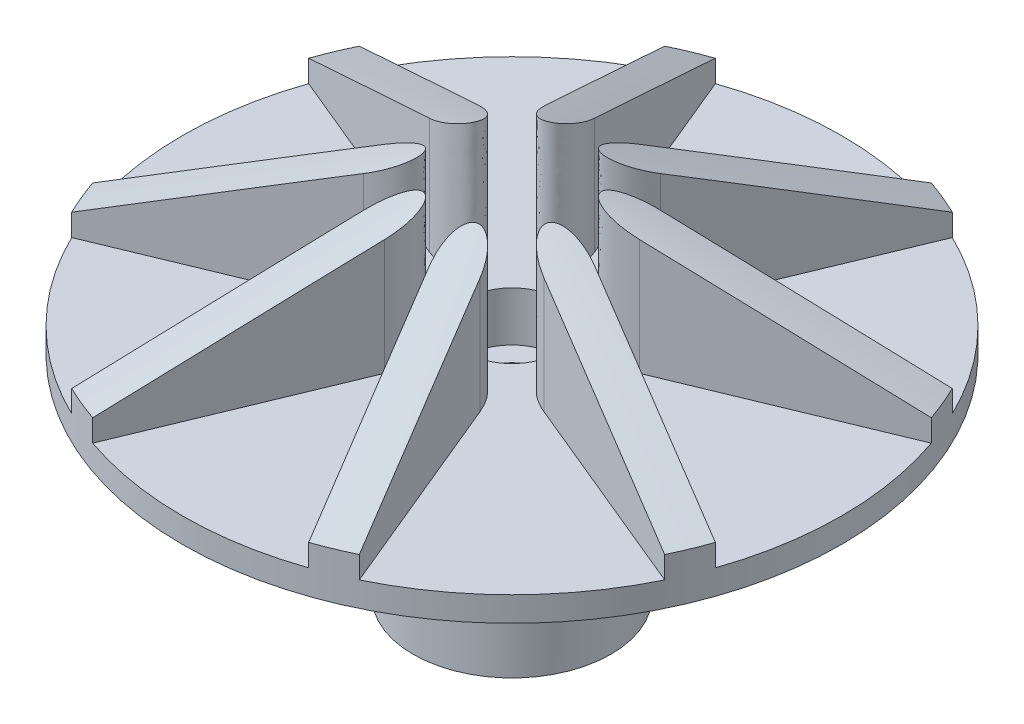
SolidWorks part; units mm, degrees
ref_plane "Front Plane" through (0, 0, 0) normal (0, 0, 1) x (1, 0, 0)
ref_plane "Top Plane" through (0, 0, 0) normal (0, 1, 0) x (1, 0, 0)
ref_plane "Right Plane" through (0, 0, 0) normal (1, 0, 0) x (0, 0, -1)
sketch "Sketch1" plane through (0, 0, 0) normal (0, 1, 0) x (1, 0, 0)
  circle A0 centre (0, 0) radius 26.6319
  dimension "D1" = 53.2638
extrude "impeller plate" add sketch "Sketch1" along normal blind 2
sketch "Sketch6" plane through (0, 0, 0) normal (0, -1, 0) x (-1, 0, 0)
  circle A0 centre (0, 0) radius 8
  dimension "D1" = 16
extrude "boss" add sketch "Sketch6" along normal blind 17
sketch "Sketch7" plane through (0, -17, 0) normal (0, -1, 0) x (-1, 0, 0)
  circle A0 centre (0, 0) radius 2
  dimension "D1" = 4
extrude "bolt bore" cut sketch "Sketch7" against normal through all
sketch "Sketch8" plane through (0, -17, 0) normal (0, -1, 0) x (-1, 0, 0)
  circle A0 centre (0, 0) radius 4
  dimension "D1" = 8
extrude "shaft bore" cut sketch "Sketch8" against normal blind 12
sketch "Sketch9" plane through (0, 2, 0) normal (0, 1, 0) x (1, 0, 0)
  circle A0 centre (0, 0) radius 3.75
  dimension "D1" = 7.5
extrude "bolt head bore" cut sketch "Sketch9" against normal blind 4
sketch "Sketch11" plane through (0, -17, 0) normal (0, -1, 0) x (1, 0, 0)
  line L1 (-6, 1) -> (6, 1)
  line L2 (-6, 1) -> (-6, -1)
  line L3 (-6, -1) -> (6, -1)
  line L4 (6, 1) -> (6, -1)
  line L5 (-6, 1) -> (6, -1) construction
  line L6 (-6, -1) -> (6, 1) construction
  point P0 (0, 0)
  dimension "D1" = 12
  dimension "D2" = 2
extrude "dowel slot" cut sketch "Sketch11" against normal blind 3
sketch "Sketch12" plane through (0, 2, 0) normal (0, 1, 0) x (1, 0, 0)
  line L0 (0, 0) -> (26.6319, 0) construction
  line L1 (5.2287, 1.3897) -> (26.5956, 1.3897)
  line L2 (5.2287, -1.3897) -> (26.5956, -1.3897)
  circle A0 centre (0, 0) radius 26.6319 construction
  arc A3 (26.5956, -1.3897) -> (26.5956, 1.3897) centre (0, 0) ccw
  arc A4 (5.2287, -1.3897) -> (5.2287, 1.3897) centre (0, 0) ccw
  dimension "D3" = 10.8204
  dimension "D1" = 1.3897
  dimension "D2" = 1.3897
extrude "opening alingment cut" cut sketch "Sketch12" against normal blind 1
pattern_circular "opening alingment pattern" count 8 over 360 about axis through (0, 0, 0) along (0, 1, 0) of "opening alingment cut"
sketch "Sketch14" plane through (0, 2, 0) normal (0, 1, 0) x (1, 0, 0)
  line L0 (0, 0) -> (26.6319, 0) construction
  line L1 (26.5956, 1.3897) -> (5.2287, 1.3897) construction
  line L2 (7.2942, 4.7175) -> (8.4935, 1.822) construction
  line L3 (25.1617, 8.7262) -> (8.4935, 1.822) construction
  line L4 (7.8938, 3.2697) -> (4.9984, 2.0704) construction
  line L5 (0, 0) -> (24.6047, 10.1916) construction
  line L7 (7.2942, 4.7175) -> (23.9624, 11.6217)
  line L9 (8.4935, 1.822) -> (25.1617, 8.7262)
  arc A2 (26.5956, -1.3897) -> (26.5956, 1.3897) centre (0, 0) ccw construction
  arc A5 (26.5956, 1.3897) -> (19.7886, 17.8232) centre (0, 0) ccw construction
  circle A6 centre (0, 0) radius 5.4102 construction
  circle A7 centre (0, 0) radius 5.4102 construction
  arc A8 (25.1617, 8.7262) -> (23.9624, 11.6217) centre (0, 0) ccw
  ellipse E0 centre (7.8938, 3.2697) end of major axis (10.7893, 4.4691) minor radius 1.567 (7.2942, 4.7175) -> (8.4935, 1.822) ccw
  dimension "D1" = 22.5
extrude "one blade" add sketch "Sketch14" along normal blind 10.7467
sketch "Sketch15" plane through (0, 2, 0) normal (0, 1, 0) x (1, 0, 0)
  circle A0 centre (0, 0) radius 26.6319
  arc A1 (-19.7886, 17.8232) -> (-26.5956, 1.3897) centre (0, 0) ccw construction
  circle A2 centre (0, 0) radius 3.75
  circle A3 centre (0, 0) radius 3.75 construction
extrude "opening alignment fill" add sketch "Sketch15" against normal blind 2
pattern_circular "CirPattern2" count 8 over 360 of "one blade"
sketch "Sketch16" plane through (0, 0, 0) normal (1, 0, 0) x (0, 0, -1)
  line L0 (0, 0) -> (0, 12.7467) construction
  line L2 (26.6319, 0) -> (26.6319, 3.778) construction
  line L3 (0, 12.7467) -> (5.4102, 12.7467) construction
  line L4 (5.4102, 12.7467) -> (26.6319, 3.778)
  line L5 (26.6319, 3.778) -> (26.6319, 12.7467)
  line L6 (26.6319, 12.7467) -> (5.4102, 12.7467)
  line L7 (-26.6319, 0) -> (26.6319, 0) construction
  dimension "D1" = 3.778
  dimension "D2" = 5.4102
  dimension "D3" = 26.6319
  dimension "D4" = 12.7467
revolve "angle cut" cut sketch "Sketch16" angle 360 about L0
equation "\"big seal ID\"= 16mm"
equation "\"z\" = 8 \t\t\t'number of blades"
equation "\"de_length\" = 10mm\t\t'entrance eye consistent length"
equation "\"av\" = \"ae\"*\"av_ratio\"\t\t'area between just two blades"
equation "\"d2\" = 2.097in \t\t\t'outer diameter of the impeller"
equation "\"d_exit\" = 0.18in \t\t'volute throat aka D4"
equation "\"theta\" = 25\t\t\t'angle of blades from inner to outer "
equation "\"b2\" = .07in\t\t\t\t\t\t\t'tip height from disc surface at d2"
equation "\"b1\" = \"b2\" + (\"d2\"/2 - \"de\"/2)*sin(\"theta\") \t\t\t'tip height from disc surface at inlet eye"
equation "\"impeller base thickness\"= 2mm"
equation "\"impeller dowel diameter\" = 2mm"
equation "\"impeller bolt head diameter\" = 7.5mm"
equation "\"impeller bolt head depth\" = 4mm"
equation "\"impeller bolt stop depth\" = 3mm"
equation "\"impeller bolt bore\" = 4mm"
equation "\"impeller shaft bore depth\" = 12mm"
equation "\"impeller shaft bore\" = 8mm"
equation "\"impeller boss depth\" = \"impeller shaft bore depth\"+\"impeller bolt stop depth\"+\"impeller bolt head depth\"-\"impeller base thickness\""
equation "\"impeller boss diameter\" = 16mm"
equation "\"impeller dowel length\" = 2mm*2 + \"impeller shaft bore\""
equation "\"D1@Sketch1\"=\"d2\""
equation "\"D1@impeller plate\" = \"impeller base thickness\""
equation "\"D1@Sketch6\"=\"impeller boss diameter\""
equation "\"D1@boss\" = \"impeller boss depth\""
equation "\"D1@Sketch7\"=\"impeller bolt bore\""
equation "\"D1@Sketch8\"= \"impeller shaft bore\""
equation "\"D1@shaft bore\" = \"impeller shaft bore depth\""
equation "\"D1@Sketch9\"=\"impeller bolt head diameter\""
equation "\"D1@bolt head bore\" = \"impeller bolt head depth\""
equation "\"D1@Sketch11\"=\"impeller dowel length\""
equation "\"D2@Sketch11\"=\"impeller dowel diameter\""
equation "\"D1@dowel slot\" = \"impeller dowel diameter\" + 1mm"
equation "\"ae\" = 3.14*(\"de\"^2)/4\t\t'entrance eye area'"
equation "\"av_ratio\" = .325\t\t'ratio of av/ae at N_s of 470, range is .275 to .375, .325 ideal. High ratio means bigger area means smaller blades"
equation "\"s_open\" = \"av\"/\"b1\"\t\t'width of open area"
equation "\"de\" = 0.426in\t\t\t'entrance eye diameter"
equation "\"ce\" = 3.14*\"de\"\t\t'entrance eye circumference"
equation "\"D1@Sketch12\"=\"s_open\"/2"
equation "\"D3@Sketch12\"=\"de\""
equation "\"D1@opening alingment pattern\" = \"z\""
equation "\"D2@Sketch12\"=\"s_open\"/2"
equation "\"D1@one blade\" = \"b1\""
equation "\"D1@opening alignment fill\" = \"impeller base thickness\""
equation "\"D1@CirPattern2\"=\"z\""
equation "\"D1@Sketch16\"=\"impeller base thickness\"+\"b2\""
equation "\"D2@Sketch16\"=\"de\"/2"
equation "\"D3@Sketch16\"=\"d2\"/2"
equation "\"D1@Sketch14\"=360/\"z\"/2"
equation "\"D4@Sketch16\"=\"b1\"+\"impeller base thickness\""
equation "\"s\"=\"ce\" - \"z\"*\"s_open\""
